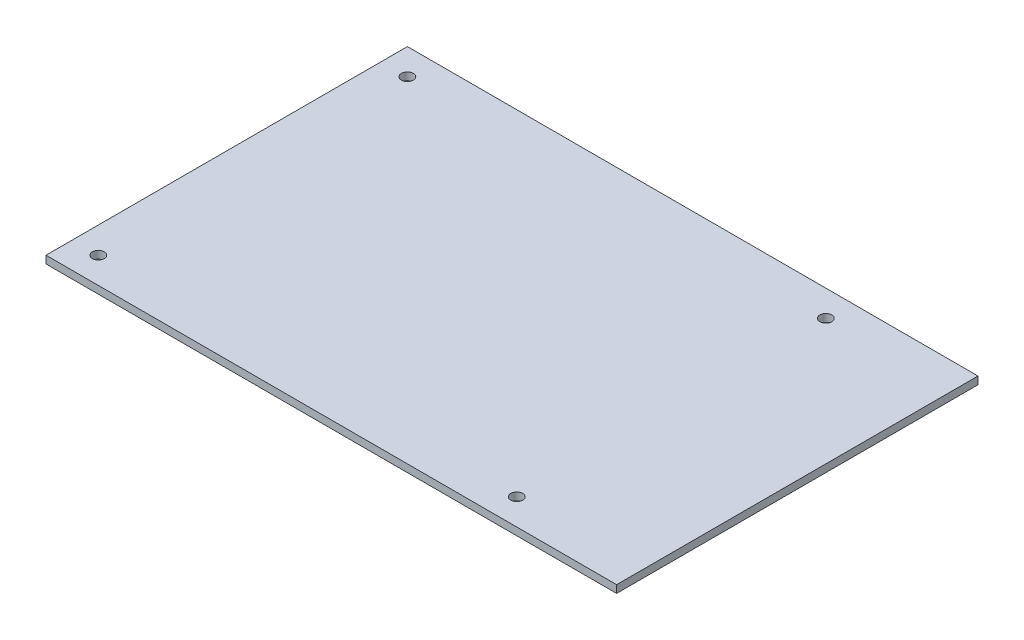
SolidWorks part; units mm, degrees
ref_plane "Front Plane" through (0, 0, 0) normal (0, 0, 1) x (1, 0, 0)
ref_plane "Top Plane" through (0, 0, 0) normal (0, 1, 0) x (1, 0, 0)
ref_plane "Right Plane" through (0, 0, 0) normal (1, 0, 0) x (0, 0, -1)
sketch "Sketch1" plane through (0, 0, 0) normal (0, 1, 0) x (1, 0, 0)
  line L1 (60, -38) -> (-60, -38)
  line L2 (60, -38) -> (60, 38)
  line L3 (60, 38) -> (-60, 38)
  line L4 (-60, -38) -> (-60, 38)
  line L5 (60, -38) -> (-60, 38) construction
  line L6 (60, 38) -> (-60, -38) construction
  point P0 (0, 0)
  dimension "D1" = 76
  dimension "D2" = 120
extrude "Boss-Extrude1" add sketch "Sketch1" against normal blind 1.6
sketch "Sketch2" plane through (0, 0, 0) normal (0, 1, 0) x (1, 0, 0)
  line L0 (-67.82, 32.5) -> (71.0218, 32.5) construction
  line L1 (-68.9843, -32.5) -> (73.2049, -32.5) construction
  line L2 (-68.9843, 0) -> (73.2049, 0) construction
  line L3 (-54.5, 44.0248) -> (-54.5, -43.8793) construction
  line L4 (-60, 38) -> (-60, -38) construction
  line L5 (33.5, 44.0248) -> (33.5, -48.0998) construction
  circle A0 centre (-54.5, 32.5) radius 1.25
  circle A1 centre (-54.5, -32.5) radius 1.25
  circle A2 centre (33.5, 32.5) radius 1.25
  circle A3 centre (33.5, -32.5) radius 1.25
  dimension "D3" = 2.5
  dimension "D1" = 65
  dimension "D2" = 5.5
  dimension "D4" = 88
extrude "Cut-Extrude1" cut sketch "Sketch2" against normal through all
